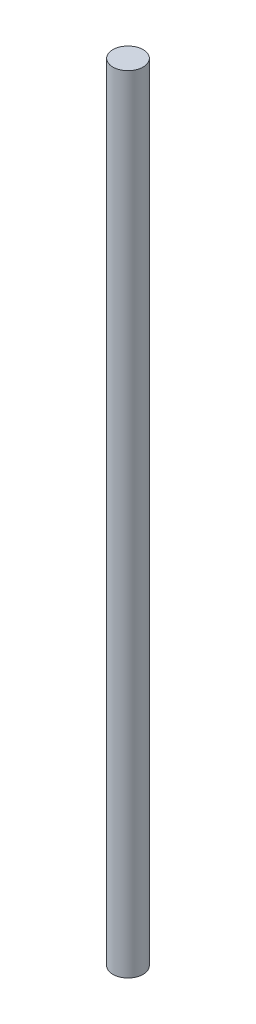
SolidWorks part; units mm, degrees
material "1023 Carbon Steel Sheet (SS)"
ref_plane "Front Plane" through (0, 0, 0) normal (0, 0, 1) x (1, 0, 0)
ref_plane "Top Plane" through (0, 0, 0) normal (0, 1, 0) x (1, 0, 0)
ref_plane "Right Plane" through (0, 0, 0) normal (1, 0, 0) x (0, 0, -1)
sketch "Sketch1" plane through (0, 0, 0) normal (0, 1, 0) x (1, 0, 0)
  circle A0 centre (0, 0) radius 1.5
  dimension "D1" = 3
extrude "Boss-Extrude1" add sketch "Sketch1" along normal blind 78
